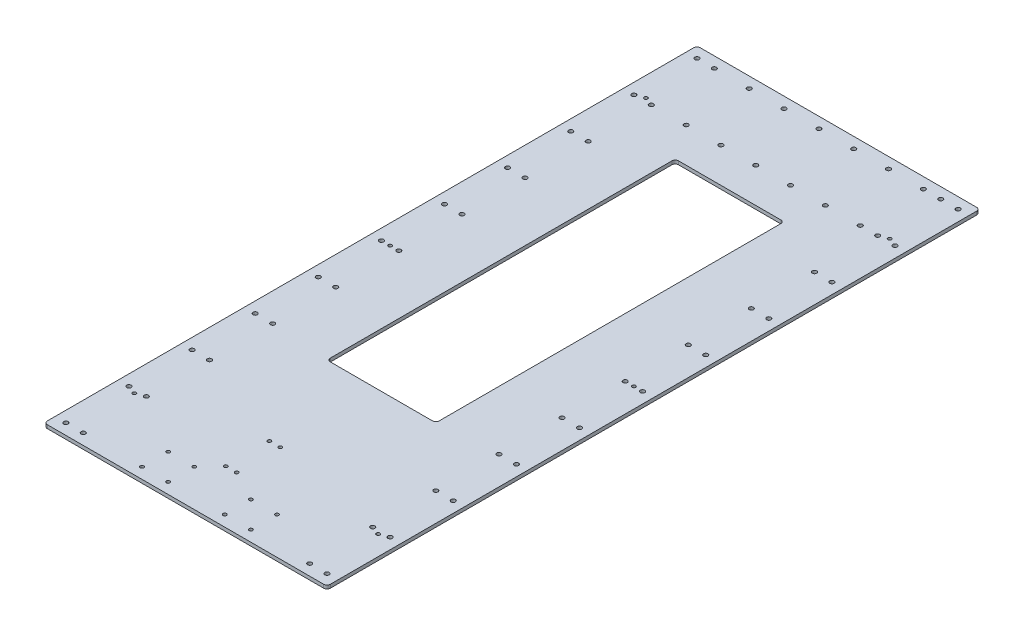
SolidWorks part; units mm, degrees
other "Markup1"
sketch "Sketch2" plane through (-130, 3.175, -300) normal (0, 1, 0) x (1, 0, 0)
ref_plane "Front Plane" through (0, 0, 0) normal (0, 0, 1) x (1, 0, 0)
ref_plane "Top Plane" through (0, 0, 0) normal (0, 1, 0) x (1, 0, 0)
ref_plane "Right Plane" through (0, 0, 0) normal (1, 0, 0) x (0, 0, -1)
sketch "Sketch1" plane through (0, 0, 0) normal (0, 1, 0) x (1, 0, 0)
  line L0 (0, 300) -> (0, -300) construction
  line L1 (-130, -300) -> (130, -300)
  line L2 (-130, -300) -> (-130, 300)
  line L3 (-130, 300) -> (130, 300)
  line L4 (130, -300) -> (130, 300)
  line L5 (-130, -300) -> (130, 300) construction
  line L6 (-130, 300) -> (130, -300) construction
  line L9 (-50, 200) -> (50, 200)
  line L10 (50, -120) -> (50, 200)
  line L11 (112, -300) -> (112, 300) construction
  line L12 (-38, -249.1372) -> (-38, -296.0221) construction
  line L13 (-130, 0) -> (130, 0) construction
  line L14 (-50, -120) -> (50, -120)
  line L15 (-50, -120) -> (-50, 200)
  line L16 (-33.8134, -231) -> (-9.1079, -231) construction
  line L17 (-91.9691, -278) -> (98.2286, -278) construction
  circle A0 centre (120, 290) radius 2
  circle A1 centre (120, 232) radius 2
  circle A2 centre (120, 174) radius 2
  circle A3 centre (120, 116) radius 2
  circle A4 centre (120, 58) radius 2
  circle A5 centre (120, 0) radius 2
  circle A6 centre (120, -58) radius 2
  circle A7 centre (120, -116) radius 2
  circle A8 centre (120, -174) radius 2
  circle A9 centre (120, -232) radius 2
  circle A10 centre (120, -290) radius 2
  circle A11 centre (-120, 232) radius 2
  circle A12 centre (-120, -290) radius 2
  circle A13 centre (-120, -232) radius 2
  circle A14 centre (-120, -174) radius 2
  circle A15 centre (-120, -116) radius 2
  circle A16 centre (-120, -58) radius 2
  circle A17 centre (-120, 0) radius 2
  circle A18 centre (-120, 58) radius 2
  circle A19 centre (-120, 116) radius 2
  circle A20 centre (-120, 174) radius 2
  circle A21 centre (-120, 290) radius 2
  circle A22 centre (112, 235) radius 1.6
  circle A23 centre (-112, 235) radius 1.6
  circle A24 centre (112, -235) radius 1.6
  circle A25 centre (-112, -235) radius 1.6
  circle A26 centre (104, 290) radius 2
  circle A27 centre (104, 232) radius 2
  circle A28 centre (104, 174) radius 2
  circle A29 centre (104, 116) radius 2
  circle A30 centre (104, 58) radius 2
  circle A31 centre (104, 0) radius 2
  circle A32 centre (104, -58) radius 2
  circle A33 centre (104, -116) radius 2
  circle A34 centre (104, -174) radius 2
  circle A35 centre (104, -232) radius 2
  circle A36 centre (104, -290) radius 2
  circle A37 centre (-104, -290) radius 2
  circle A38 centre (-104, -174) radius 2
  circle A39 centre (-104, -116) radius 2
  circle A40 centre (-104, -58) radius 2
  circle A41 centre (-104, 0) radius 2
  circle A42 centre (-104, 58) radius 2
  circle A43 centre (-104, 116) radius 2
  circle A44 centre (-104, 174) radius 2
  circle A45 centre (-104, 232) radius 2
  circle A46 centre (-104, 290) radius 2
  circle A47 centre (-104, -232) radius 2
  circle A48 centre (112, 0) radius 1.6
  circle A49 centre (-112, 0) radius 1.6
  circle A50 centre (-50, -290) radius 1.6
  circle A51 centre (-50, -266) radius 1.6
  circle A52 centre (50, -266) radius 1.6
  circle A53 centre (50, -290) radius 1.6
  circle A54 centre (-26, -290) radius 1.6
  circle A55 centre (-26, -266) radius 1.6
  circle A56 centre (26, -290) radius 1.6
  circle A57 centre (26, -266) radius 1.6
  circle A58 centre (-72, 290) radius 2
  circle A59 centre (-72, 232) radius 2
  circle A60 centre (-40, 290) radius 2
  circle A61 centre (-40, 232) radius 2
  circle A62 centre (-8, 290) radius 2
  circle A63 centre (-8, 232) radius 2
  circle A64 centre (24, 290) radius 2
  circle A65 centre (24, 232) radius 2
  circle A66 centre (56, 290) radius 2
  circle A67 centre (56, 232) radius 2
  circle A68 centre (88, 290) radius 2
  circle A69 centre (88, 232) radius 2
  circle A73 centre (-12, -251) radius 1.6
  circle A75 centre (-2, -251) radius 1.6
  circle A76 centre (-12, -211) radius 1.6
  circle A77 centre (-2, -211) radius 1.6
  circle A78 centre (120, 232) radius 2 [skipped]
  circle A79 centre (120, 290) radius 2 [skipped]
  point P0 (0, 0)
  point P6 (0, 0)
  dimension "D3" = 4
  dimension "D7" = 3.2
  dimension "D11" = 4
  dimension "D17" = 3.2
  dimension "D18" = 3.2
  dimension "D19" = 3.2
  dimension "D25" = 3.2
  dimension "D21" = 3.2
  dimension "D1" = 600
  dimension "D4" = 10
  dimension "D5" = 10
  dimension "D9" = 100
  dimension "D12" = 16
  dimension "D10" = 120
  dimension "D14" = 200
  dimension "D15" = 10
  dimension "D16" = 8
  dimension "D8" = 235
  dimension "D22" = 10
  dimension "D23" = 12
  dimension "D26" = 10
  dimension "D30" = 12
  dimension "D27" = 20
  dimension "D28" = 20
  dimension "D32" = 47
  dimension "D33" = 38
  dimension "D34" = 260
  dimension "D20" = 12
  dimension "D29" = 12
  dimension "D31" = 12
  dimension "D6" = 11
  dimension "D13" = 11
  dimension "D24" = 8
extrude "Boss-Extrude1" add sketch "Sketch1" along normal blind 3.175
fillet "Fillet1" radius 3 8 edges at (50, 1.5875, -200) (-130, 1.5875, 300) (130, 1.5875, 300) (130, 1.5875, -300) (-130, 1.5875, -300) (-50, 1.5875, -200) (-50, 1.5875, 120) (50, 1.5875, 120)
equation "\"width\"=250"
equation "\"length\"= 600"
equation "\"D1@Sketch1\"=\"length\""
equation "\"m3\"= 3.2"
